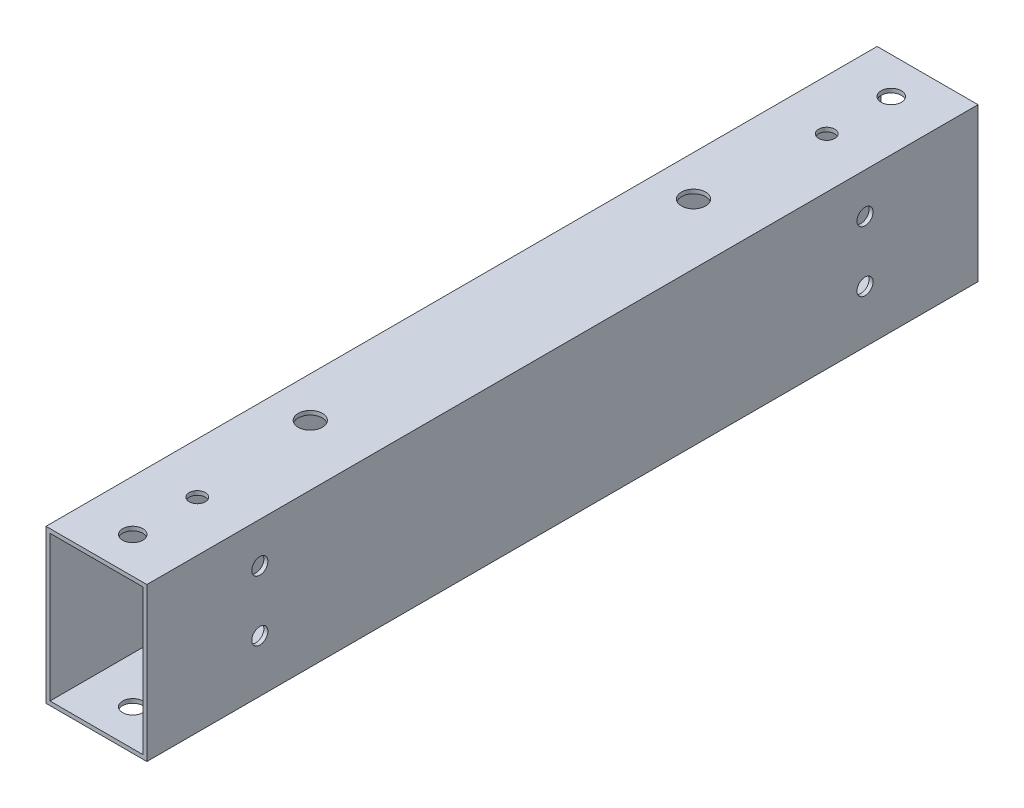
SolidWorks part; units mm, degrees
material "6061 合金"
ref_plane "前视基准面" through (0, 0, 0) normal (0, 0, 1) x (1, 0, 0)
ref_plane "上视基准面" through (0, 0, 0) normal (0, 1, 0) x (1, 0, 0)
ref_plane "右视基准面" through (0, 0, 0) normal (1, 0, 0) x (0, 0, -1)
sketch "草图1" plane through (0, 0, 0) normal (0, 0, 1) x (1, 0, 0)
  line L1 (-12.5, 19) -> (12.5, 19)
  line L2 (-12.5, 19) -> (-12.5, -19)
  line L3 (-12.5, -19) -> (12.5, -19)
  line L4 (12.5, 19) -> (12.5, -19)
  line L5 (-12.5, 19) -> (12.5, -19) construction
  line L6 (-12.5, -19) -> (12.5, 19) construction
  line L7 (-11.5, 18) -> (11.5, 18)
  line L8 (-11.5, 18) -> (-11.5, -18)
  line L9 (-11.5, -18) -> (11.5, -18)
  line L10 (11.5, 18) -> (11.5, -18)
  line L11 (-11.5, 18) -> (11.5, -18) construction
  line L12 (-11.5, -18) -> (11.5, 18) construction
  point P0 (0, 0)
  point P6 (0, 0)
  dimension "D1" = 25
  dimension "D2" = 38
  dimension "D3" = 23
  dimension "D4" = 36
extrude "凸台-拉伸1" add sketch "草图1" along normal mid plane 206
sketch "草图2" plane through (0, 19, 0) normal (0, 1, 0) x (1, 0, 0)
  line L0 (12.5, 103) -> (-12.5, 103) construction
  line L1 (0, 0) -> (0, 94) construction
  circle A0 centre (0, 94) radius 2.5
  circle A1 centre (0, 78) radius 2
  dimension "D1" = 9
  dimension "D2" = 5
  dimension "D3" = 4
  dimension "D4" = 16
extrude "切除-拉伸1" cut sketch "草图2" against normal blind 40
mirror "镜向1" about plane through (0, 0, 0) normal (0, 0, 1) of "切除-拉伸1"
sketch "草图4" plane through (0, 19, 0) normal (0, 1, 0) x (1, 0, 0)
  line L0 (-2.5, 0) -> (-2.5, 47.5) construction
  line L1 (-2.5, 0) -> (-2.5, -47.5) construction
  circle A0 centre (-2.5, 47.5) radius 3
  circle A2 centre (-2.5, -47.5) radius 3
  dimension "D1" = 6
  dimension "D2" = 95
  dimension "D3" = 6
  dimension "D4" = 47.5
  dimension "D5" = 2.5
extrude "切除-拉伸2" cut sketch "草图4" along direction (0, 1, 0) on the side against the normal up to surface (38 mm away)
sketch "草图5" plane through (12.5, 0, 0) normal (1, 0, 0) x (0, 0, -1)
  line L0 (0, 42.8851) -> (0, -37.3448) construction
  line L1 (-103, 19) -> (103, 19) construction
  circle A0 centre (-75, 9) radius 2
  circle A1 centre (-75, -6) radius 2
  circle A2 centre (75, -6) radius 2
  circle A3 centre (75, 9) radius 2
  dimension "D2" = 4
  dimension "D3" = 10
  dimension "D4" = 15
  dimension "D5" = 150
extrude "切除-拉伸3" cut sketch "草图5" against normal through all
